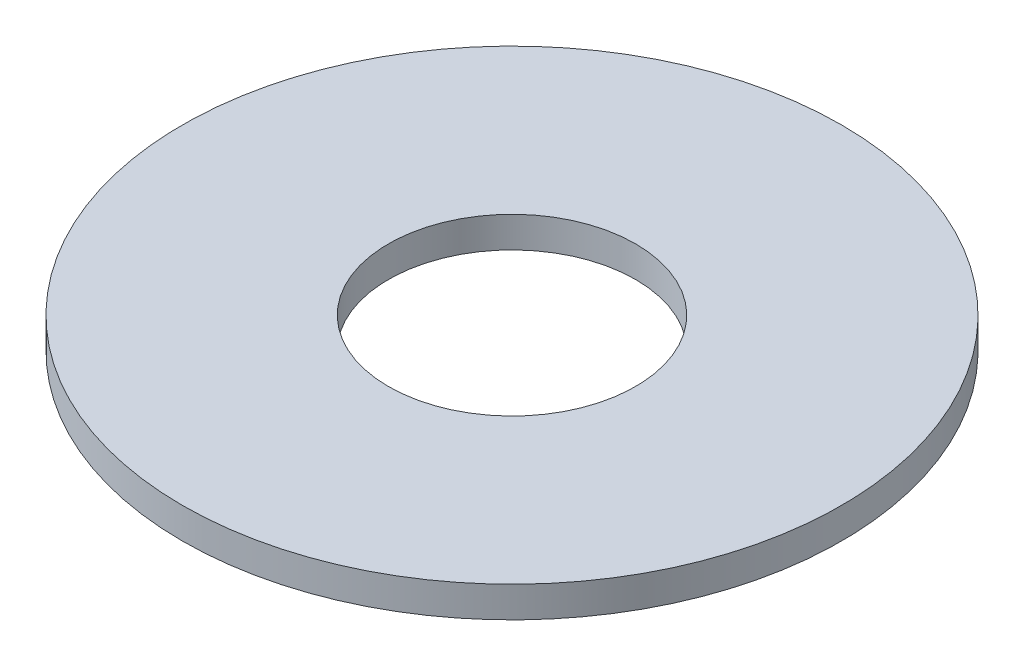
SolidWorks part; units mm, degrees
ref_plane "Front Plane" through (0, 0, 0) normal (0, 0, 1) x (1, 0, 0)
ref_plane "Top Plane" through (0, 0, 0) normal (0, 1, 0) x (1, 0, 0)
ref_plane "Right Plane" through (0, 0, 0) normal (1, 0, 0) x (0, 0, -1)
sketch "Sketch1" plane through (0, 0, 0) normal (0, 1, 0) x (1, 0, 0)
  circle A0 centre (0, 0) radius 16
  circle A1 centre (0, 0) radius 6
extrude "Boss-Extrude1" add sketch "Sketch1" along normal blind 1.5
